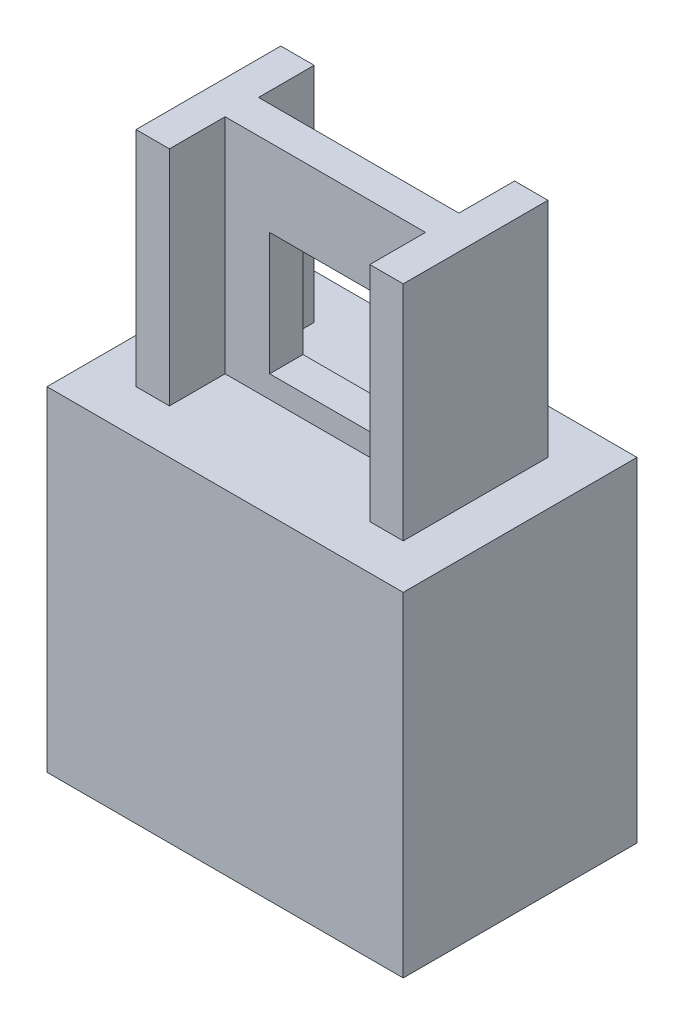
SolidWorks part; units mm, degrees
ref_plane "Front Plane" through (0, 0, 0) normal (0, 0, 1) x (1, 0, 0)
ref_plane "Top Plane" through (0, 0, 0) normal (0, 1, 0) x (1, 0, 0)
ref_plane "Right Plane" through (0, 0, 0) normal (1, 0, 0) x (0, 0, -1)
sketch "Sketch1" plane through (0, 0, 0) normal (0, 1, 0) x (1, 0, 0)
  line L1 (-6, 3.25) -> (6, 3.25)
  line L2 (-6, 3.25) -> (-6, -3.25)
  line L3 (-6, -3.25) -> (6, -3.25)
  line L4 (6, 3.25) -> (6, -3.25)
  line L5 (-6, 3.25) -> (6, -3.25) construction
  line L6 (-6, -3.25) -> (6, 3.25) construction
  point P0 (0, 0)
  dimension "D1" = 12
  dimension "D2" = 6.5
extrude "Boss-Extrude1" add sketch "Sketch1" along normal blind 10
sketch "Sketch2" plane through (0, 0, 0) normal (0, 1, 0) x (1, 0, 0)
  line L8 (8, -5.25) -> (8, 5.25)
  line L9 (8, 5.25) -> (-8, 5.25)
  line L10 (-8, 5.25) -> (-8, -5.25)
  line L11 (-8, -5.25) -> (8, -5.25)
  line L12 (8, -5.25) -> (8, 5.25)
  line L13 (8, 5.25) -> (-8, 5.25)
  line L14 (-8, 5.25) -> (-8, -5.25)
  line L15 (-8, -5.25) -> (8, -5.25)
  dimension "D1" = 2
extrude "Boss-Extrude2" add sketch "Sketch2" against normal blind 15
sketch "Sketch3" plane through (0, 10, 0) normal (0, 1, 0) x (1, 0, 0)
  line L0 (6, 3.25) -> (-6, 3.25) construction
  line L1 (-4.5, 3.25) -> (4.5, 3.25)
  line L2 (-4.5, 3.25) -> (-4.5, 0.75)
  line L3 (-4.5, 0.75) -> (4.5, 0.75)
  line L4 (4.5, 3.25) -> (4.5, 0.75)
  line L5 (-6, -3.25) -> (6, -3.25) construction
  line L6 (-4.5, -3.25) -> (4.5, -3.25)
  line L7 (-4.5, -3.25) -> (-4.5, -0.75)
  line L8 (-4.5, -0.75) -> (4.5, -0.75)
  line L9 (4.5, -3.25) -> (4.5, -0.75)
  line L10 (-6, 3.25) -> (-6, -3.25) construction
  line L11 (6, -3.25) -> (6, 3.25) construction
  line L12 (-4.5, 0.75) -> (-4.5, -0.75) construction
  point P16 (-4.5, 0)
  dimension "D1" = 1.5
  dimension "D2" = 1.5
  dimension "D3" = 1.5
extrude "Cut-Extrude1" cut sketch "Sketch3" against normal blind 10
sketch "Sketch4" plane through (0, 0, -0.75) normal (0, 0, -1) x (-1, 0, 0)
  line L1 (-2.5, 1) -> (2.5, 1)
  line L2 (-2.5, 1) -> (-2.5, 6.5)
  line L3 (-2.5, 6.5) -> (2.5, 6.5)
  line L4 (2.5, 1) -> (2.5, 6.5)
  point P5 (0, 0)
  point P6 (-4.803, 8.5504)
  point P7 (0, 0)
  point P9 (2.4716, 2.0208)
  point P12 (0, 1)
  point P13 (-2.5, 2.2853)
  dimension "D1" = 6.5
  dimension "D2" = 5
  dimension "D3" = 1
extrude "Cut-Extrude2" cut sketch "Sketch4" against normal through all both and the other way through all contours L3 L4 L1 L2
